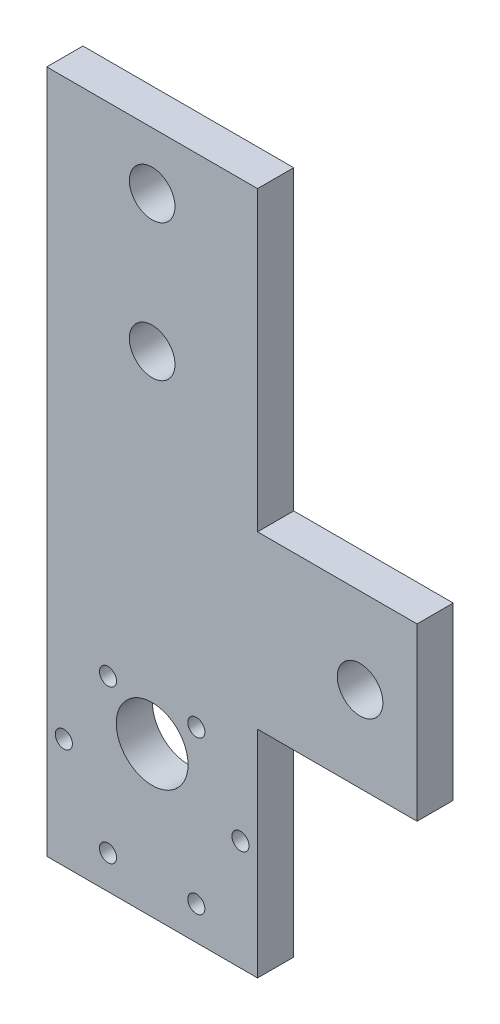
SolidWorks part; units mm, degrees
ref_plane "Front Plane" through (0, 0, 0) normal (0, 0, 1) x (1, 0, 0)
ref_plane "Top Plane" through (0, 0, 0) normal (0, 1, 0) x (1, 0, 0)
ref_plane "Right Plane" through (0, 0, 0) normal (1, 0, 0) x (0, 0, -1)
sketch "Sketch1" plane through (0, 0, 0) normal (0, 0, 1) x (1, 0, 0)
  line L0 (-18.5, 18.5) -> (18.5, 18.5) construction
  line L1 (-18.5, 100.675) -> (18.5, 100.675)
  line L2 (-18.5, 100.675) -> (-18.5, -19.325)
  line L3 (-18.5, -19.325) -> (18.5, -19.325)
  line L4 (18.5, 100.675) -> (18.5, 48.5)
  line L9 (18.5, 18.5) -> (18.5, -19.325)
  line L11 (18.5, 48.5) -> (46.5, 48.5)
  line L13 (18.5, 18.5) -> (46.5, 18.5)
  line L14 (46.5, 48.5) -> (46.5, 18.5)
  circle A1 centre (-7.75, 13.4234) radius 1.5
  circle A2 centre (7.75, 13.4234) radius 1.5
  circle A3 centre (15.5, 0) radius 1.5
  circle A4 centre (7.75, -13.4234) radius 1.5
  circle A5 centre (-7.75, -13.4234) radius 1.5
  circle A6 centre (-15.5, 0) radius 1.5
  circle A7 centre (0, 0) radius 18.5 construction
  circle A8 centre (0, 7) radius 6.3
  circle A10 centre (0, 90.675) radius 4
  circle A11 centre (0, 66.675) radius 4
  circle A12 centre (36.5, 33.5) radius 4
  point P21 (0, 0)
  dimension "D2" = 37
  dimension "D3" = 3
  dimension "D6" = 12.6
  dimension "D10" = 30
  dimension "D12" = 8
  dimension "D1" = 18.5
  dimension "D5" = 15.5
  dimension "D7" = 11.5
  dimension "D8" = 19.325
  dimension "D9" = 120
  dimension "D11" = 24
  dimension "D13" = 10
  dimension "D14" = 65
  dimension "D15" = 15
  dimension "D16" = 10
  dimension "D4" = 6
extrude "Boss-Extrude2" add sketch "Sketch1" along normal blind 6.35
